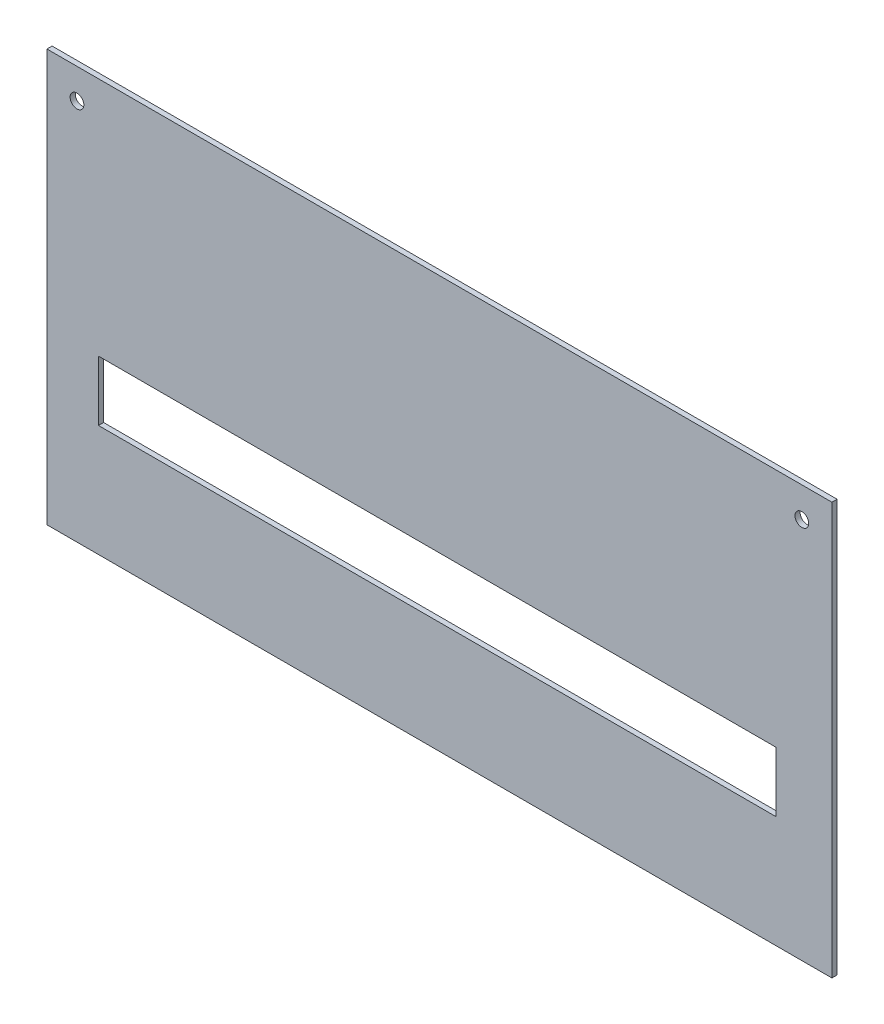
SolidWorks part; units mm, degrees
ref_plane "Front Plane" through (0, 0, 0) normal (0, 0, 1) x (1, 0, 0)
ref_plane "Top Plane" through (0, 0, 0) normal (0, 1, 0) x (1, 0, 0)
ref_plane "Right Plane" through (0, 0, 0) normal (1, 0, 0) x (0, 0, -1)
sketch "Sketch1" plane through (0, 0, 0) normal (0, 0, 1) x (1, 0, 0)
  line L1 (-228.6, 120) -> (228.6, 120)
  line L2 (-228.6, 120) -> (-228.6, -120)
  line L3 (-228.6, -120) -> (228.6, -120)
  line L4 (228.6, 120) -> (228.6, -120)
  line L5 (-228.6, 120) -> (228.6, -120) construction
  line L6 (-228.6, -120) -> (228.6, 120) construction
  point P0 (0, 0)
  dimension "D1" = 457.2
  dimension "D2" = 240
extrude "Boss-Extrude1" add sketch "Sketch1" along normal blind 3
sketch "Sketch2" plane through (0, 0, 3) normal (0, 0, 1) x (1, 0, 0)
  line L0 (-228.6, 120) -> (-228.6, -120) construction
  line L2 (228.6, -120) -> (228.6, 120) construction
  line L3 (228.6, 120) -> (-228.6, 120) construction
  circle A0 centre (-211.1, 102.5) radius 4
  circle A1 centre (211.1, 102.5) radius 4
  dimension "D1" = 8
  dimension "D3" = 8
  dimension "D2" = 17.5
  dimension "D4" = 17.5
  dimension "D5" = 17.5
  dimension "D6" = 17.5
extrude "Cut-Extrude1" cut sketch "Sketch2" against normal through all
sketch "Sketch3" plane through (0, 0, 3) normal (0, 0, 1) x (1, 0, 0)
  line L1 (-198.6, -54.9) -> (196.1, -54.9)
  line L2 (-198.6, -54.9) -> (-198.6, -19.9)
  line L3 (-198.6, -19.9) -> (196.1, -19.9)
  line L4 (196.1, -54.9) -> (196.1, -19.9)
  line L5 (228.6, -120) -> (228.6, 120) construction
  line L7 (-228.6, 120) -> (-228.6, -120) construction
  line L8 (-228.6, -120) -> (228.6, -120) construction
  dimension "D1" = 32.5
  dimension "D2" = 30
  dimension "D3" = 35
  dimension "D4" = 65.1
extrude "Cut-Extrude2" cut sketch "Sketch3" against normal through all
